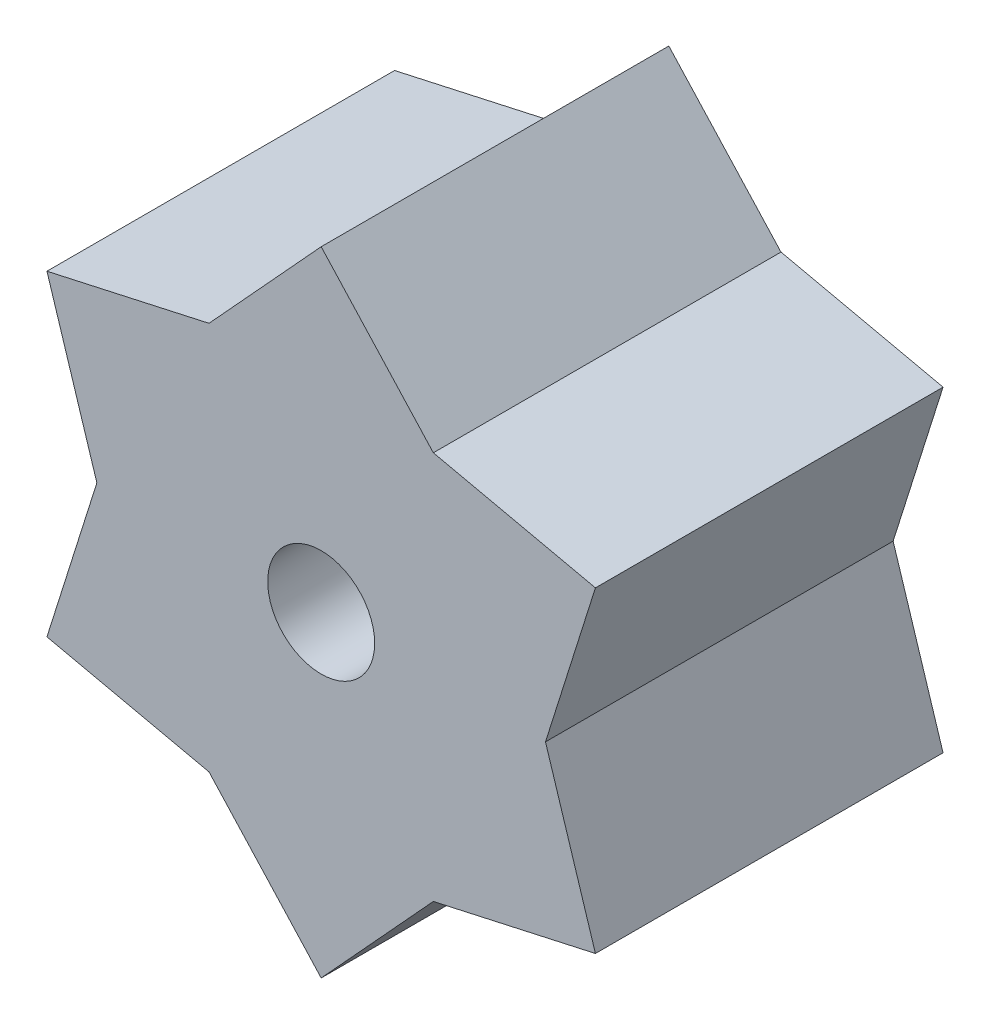
SolidWorks part; units mm, degrees
ref_plane "Front Plane" through (0, 0, 0) normal (0, 0, 1) x (1, 0, 0)
ref_plane "Top Plane" through (0, 0, 0) normal (0, 1, 0) x (1, 0, 0)
ref_plane "Right Plane" through (0, 0, 0) normal (1, 0, 0) x (0, 0, -1)
sketch "Sketch1" plane through (0, 0, 0) normal (0, 0, 1) x (1, 0, 0)
  line L0 (0, 5.9207) -> (0, -5.749) construction
  line L1 (-2.9491, 2.7024) -> (0, 5.9207)
  line L2 (0, 5.9207) -> (2.9491, 2.7024)
  line L3 (0.8658, 3.9052) -> (5.1275, 2.9604)
  line L4 (5.1275, 2.9604) -> (3.8149, -1.2028)
  line L5 (3.8149, 1.2028) -> (5.1275, -2.9604)
  line L6 (5.1275, -2.9604) -> (0.8658, -3.9052)
  line L7 (2.9491, -2.7024) -> (0, -5.9207)
  line L8 (0, -5.9207) -> (-2.9491, -2.7024)
  line L9 (-0.8658, -3.9052) -> (-5.1275, -2.9604)
  line L10 (-5.1275, -2.9604) -> (-3.8149, 1.2028)
  line L11 (-3.8149, -1.2028) -> (-5.1275, 2.9604)
  line L12 (-5.1275, 2.9604) -> (-0.8658, 3.9052)
  circle A0 centre (0, 0) radius 1
  circle A1 centre (0, 0) radius 4
  point P10 (0, 0)
  point P11 (0, 0)
  point P26 (0, 0)
  dimension "D1" = 2
  dimension "D3" = 85
  dimension "D4" = 42.5
  dimension "D2" = 3
  dimension "D5" = 6
extrude "Boss-Extrude1" add sketch "Sketch1" against normal blind 6.5
